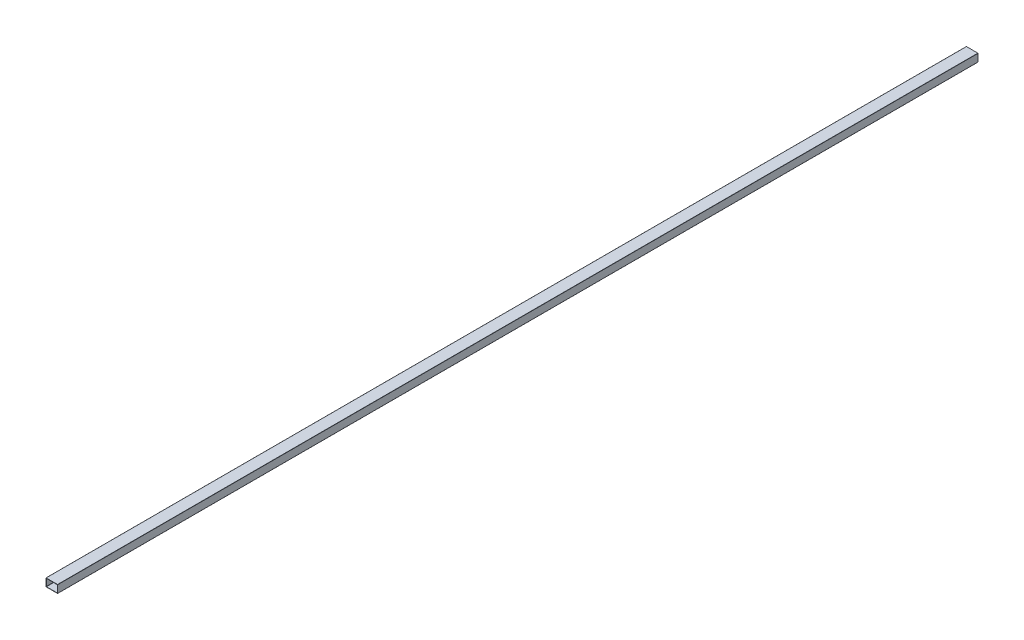
SolidWorks part; units mm, degrees
material "AISI 1035 Acero (SS)"
ref_plane "Alzado" through (0, 0, 0) normal (0, 0, 1) x (1, 0, 0)
ref_plane "Planta" through (0, 0, 0) normal (0, 1, 0) x (1, 0, 0)
ref_plane "Vista lateral" through (0, 0, 0) normal (1, 0, 0) x (0, 0, -1)
sketch "Croquis1" plane through (0, 0, 0) normal (0, 0, 1) x (1, 0, 0)
  line L0 (-36.21, -23.51) -> (-36.21, 23.51)
  line L1 (-38.1, -25.4) -> (38.1, -25.4)
  line L2 (-38.1, -25.4) -> (-38.1, 25.4)
  line L3 (-38.1, 25.4) -> (38.1, 25.4)
  line L4 (38.1, -25.4) -> (38.1, 25.4)
  line L5 (-38.1, -25.4) -> (38.1, 25.4) construction
  line L6 (-38.1, 25.4) -> (38.1, -25.4) construction
  line L7 (-36.21, 23.51) -> (36.21, 23.51)
  line L8 (36.21, -23.51) -> (36.21, 23.51)
  line L9 (-36.21, -23.51) -> (36.21, -23.51)
  point P0 (0, 0)
  dimension "D1" = 50.8
  dimension "D2" = 76.2
  dimension "D3" = 1.89
extrude "Saliente-Extruir1" add sketch "Croquis1" against normal blind 6000
fillet "Redondeo1" radius 1 8 edges at (-36.21, 23.51, -3000) (36.21, 23.51, -3000) (36.21, -23.51, -3000) (-38.1, -25.4, -3000) (-38.1, 25.4, -3000) (-36.21, -23.51, -3000) (38.1, -25.4, -3000) (38.1, 25.4, -3000)
